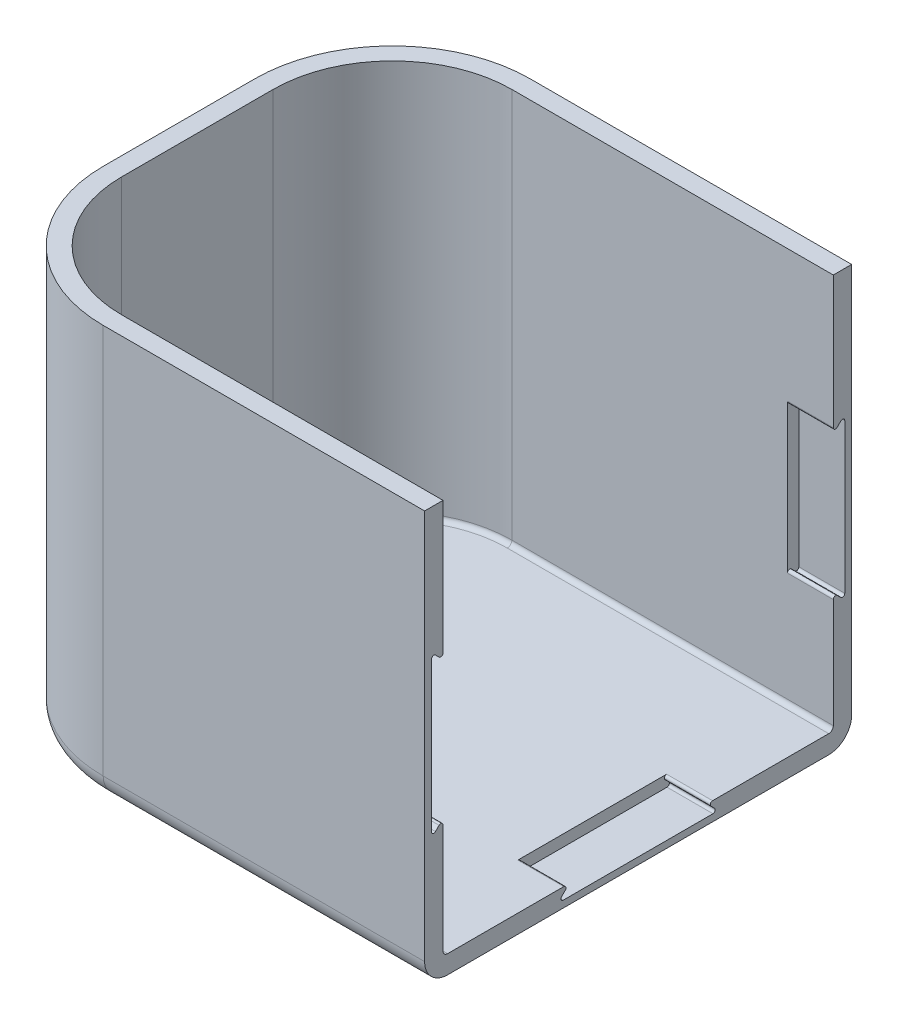
SolidWorks part; units mm, degrees
ref_plane "前基準面" through (0, 0, 0) normal (0, 0, 1) x (1, 0, 0)
ref_plane "上基準面" through (0, 0, 0) normal (0, 1, 0) x (1, 0, 0)
ref_plane "右基準面" through (0, 0, 0) normal (1, 0, 0) x (0, 0, -1)
sketch "草圖1" plane through (0, 0, 0) normal (0, 1, 0) x (1, 0, 0)
  line L0 (0, -49.5) -> (0, 49.5) construction
  line L1 (0, 46.5) -> (-100, 46.5)
  line L2 (0, 46.5) -> (0, -46.5)
  line L3 (0, -46.5) -> (-100, -46.5)
  line L4 (-100, 46.5) -> (-100, -46.5)
  dimension "D1" = 93
  dimension "D3" = 100
extrude "填料-伸長1" add sketch "草圖1" along normal blind 90
fillet "圓角8" radius 30 2 edges at (-100, 45, -46.5) (-100, 45, 46.5)
fillet "圓角9" radius 5 5 edges at (-35, 0, -46.5) (-91.2132, 0, -37.7132) (-100, 0, 0) (-91.2132, 0, 37.7132) (-35, 0, 46.5)
shell "薄殼4" thickness 4
sketch "草圖19" plane through (0, 0, -46.5) normal (0, 0, -1) x (-1, 0, 0)
  line L0 (50.325, 0) -> (-50.325, 0) construction
  line L1 (0, 49.5) -> (0, -49.5) construction
  line L2 (70, 5) -> (70, 90) construction
  circle A0 centre (15, 10) radius 3 construction
  circle A1 centre (55, 10) radius 3 construction
  dimension "D1" = 6
  dimension "D2" = 6
  dimension "D3" = 10
  dimension "D4" = 15
  dimension "D5" = 15
sketch "草圖20" plane through (0, 0, 46.5) normal (0, 0, 1) x (1, 0, 0)
  circle A0 centre (-55, 10) radius 3
  circle A1 centre (-15, 10) radius 3
extrude "除料-伸長15" [suppressed] cut sketch "草圖20" against normal up to next
sketch "草圖21" plane through (0, 0, 0) normal (1, 0, 0) x (0, 0, -1)
  line L0 (-42.5, 60) -> (42.5, 60)
  line L1 (0, 49.5) -> (0, -49.5) construction
  line L2 (42.5, 5) -> (42.5, 90) construction
  line L3 (42.5, 60) -> (45, 62.5)
  line L4 (45, 62.5) -> (45, 27.5)
  line L5 (45, 27.5) -> (42.5, 30)
  line L6 (42.5, 90) -> (42.5, 5) construction
  line L7 (42.5, 30) -> (15, 30)
  line L8 (15, 30) -> (15, 4)
  line L9 (41.5, 4) -> (16.5, 4) construction
  line L11 (17.5, 1.5) -> (-17.5, 1.5)
  line L13 (42.5, 90) -> (16.5, 90) construction
  line L15 (-41.5, 4) -> (41.5, 4) construction
  line L16 (17.5, 1.5) -> (15, 4)
  line L17 (-17.5, 1.5) -> (-15, 4)
  line L18 (-15, 30) -> (-15, 4)
  line L19 (-42.5, 30) -> (-15, 30)
  line L20 (-45, 27.5) -> (-42.5, 30)
  line L21 (-45, 62.5) -> (-45, 27.5)
  line L22 (-42.5, 60) -> (-45, 62.5)
  point P23 (0, 1.5)
  point P28 (0, 60)
  dimension "D1" = 135
  dimension "D2" = 135
  dimension "D3" = 30
  dimension "D4" = 30
  dimension "D5" = 15
  dimension "D6" = 2.5
  dimension "D7" = 2.5
  dimension "D8" = 135
extrude "除料-伸長16" cut sketch "草圖21" against normal blind 10
fillet "圓角12" radius 0.5 12 edges at (-5, 30, 42.5) (-5, 27.5, 45) (-5, 60, 42.5) (-5, 62.5, 45) (-5, 30, -42.5) (-5, 27.5, -45) (-5, 60, -42.5) (-5, 62.5, -45) (-5, 1.5, -17.5) (-5, 4, -15) (-5, 1.5, 17.5) (-5, 4, 15)
